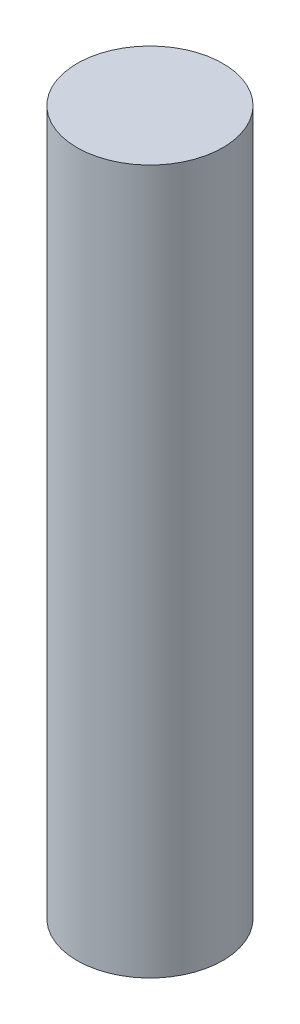
SolidWorks part; units mm, degrees
ref_plane "Front Plane" through (0, 0, 0) normal (0, 0, 1) x (1, 0, 0)
ref_plane "Top Plane" through (0, 0, 0) normal (0, 1, 0) x (1, 0, 0)
ref_plane "Right Plane" through (0, 0, 0) normal (1, 0, 0) x (0, 0, -1)
sketch "Sketch2" plane through (0, 0, 0) normal (0, 1, 0) x (1, 0, 0)
  circle A0 centre (0, 0) radius 1.45
  dimension "D1" = 2.9
extrude "Boss-Extrude1" add sketch "Sketch2" along normal blind 14
